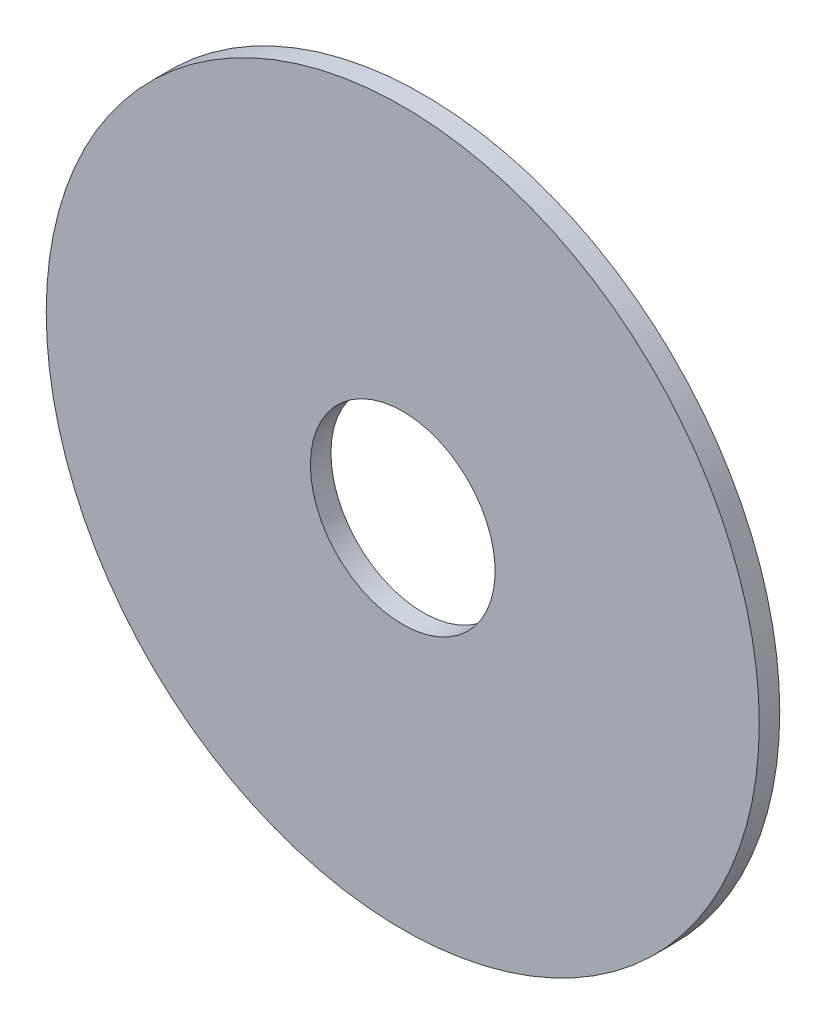
SolidWorks part; units mm, degrees
ref_plane "Front Plane" through (0, 0, 0) normal (0, 0, 1) x (1, 0, 0)
ref_plane "Top Plane" through (0, 0, 0) normal (0, 1, 0) x (1, 0, 0)
ref_plane "Right Plane" through (0, 0, 0) normal (1, 0, 0) x (0, 0, -1)
sketch "Sketch2" plane through (0, 0, 0) normal (0, 0, 1) x (1, 0, 0)
  circle A0 centre (0, 0) radius 44.1325
  dimension "D1" = 88.265
extrude "Boss-Extrude1" add sketch "Sketch2" along normal blind 2.54
sketch "Sketch3" plane through (0, 0, 0) normal (0, 0, -1) x (-1, 0, 0)
  circle A0 centre (0, 0) radius 11.43
  dimension "D1" = 22.86
extrude "Cut-Extrude1" cut sketch "Sketch3" against normal blind 2.54
